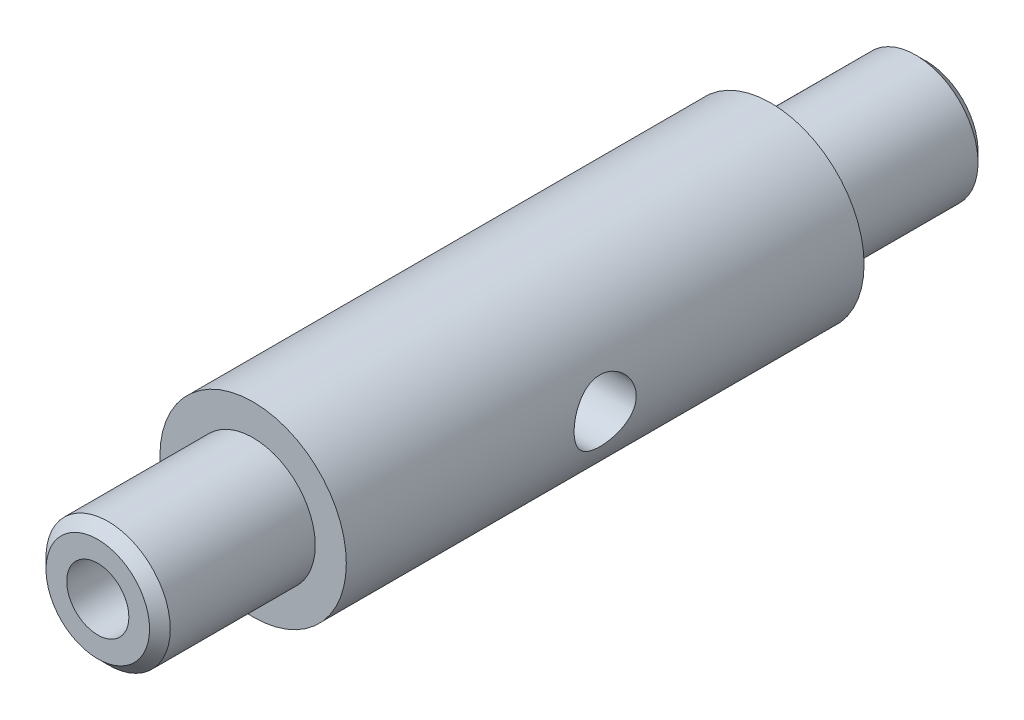
SolidWorks part; units mm, degrees
ref_plane "Front Plane" through (0, 0, 0) normal (0, 0, 1) x (1, 0, 0)
ref_plane "Top Plane" through (0, 0, 0) normal (0, 1, 0) x (1, 0, 0)
ref_plane "Right Plane" through (0, 0, 0) normal (1, 0, 0) x (0, 0, -1)
sketch "Sketch2" plane through (0, 0, 0) normal (0, 0, 1) x (1, 0, 0)
  line L0 (0, 46.8203) -> (0, -48.0606) construction
  line L1 (-48.5774, 0) -> (57.2593, 0) construction
  circle A0 centre (0, 0) radius 9
  dimension "D1" = 18
extrude "Boss-Extrude1" add sketch "Sketch2" along normal mid plane 50
sketch "Sketch3" plane through (0, 0, 25) normal (0, 0, 1) x (1, 0, 0)
  circle A0 centre (0, 0) radius 6
  dimension "D1" = 12
extrude "Boss-Extrude2" add sketch "Sketch3" along normal blind 15
sketch "Sketch4" plane through (0, 0, -25) normal (0, 0, -1) x (-1, 0, 0)
  circle A0 centre (0, 0) radius 6
  dimension "D1" = 12
extrude "Boss-Extrude4" add sketch "Sketch4" along normal blind 15 separate body contours A0
sketch "Sketch5" plane through (0, 0, 0) normal (1, 0, 0) x (0, 0, -1)
  circle A0 centre (0, 0) radius 3
  dimension "D1" = 6
extrude "Cut-Extrude1" cut sketch "Sketch5" against normal mid plane 20
sketch "Sketch6" plane through (0, 0, 40) normal (0, 0, 1) x (1, 0, 0)
  circle A0 centre (0, 0) radius 3
  dimension "D1" = 6
extrude "Cut-Extrude2" cut sketch "Sketch6" against normal blind 45
sketch "Sketch7" plane through (0, 0, 0) normal (0, 1, 0) x (1, 0, 0)
  line L0 (-3, 5) -> (0, 8)
  line L1 (-3, 5) -> (3, 5) construction
  line L2 (0, 8) -> (0, 5)
  line L3 (0, 5) -> (-3, 5)
  line L4 (0, 10.0646) -> (0, -1.4541) construction
  line L5 (-6.3147, 0) -> (6.5722, 0) construction
  point P10 (0, 0)
  dimension "D1" = 45
  dimension "D2" = 3
revolve "Cut-Revolve1" cut sketch "Sketch7" angle 360 about L4
chamfer "Chamfer1" distance 1 angle 45 1 edges at (6, 0, 40)
chamfer "Chamfer2" distance 1 angle 45 1 edges at (-6, 0, -40)
